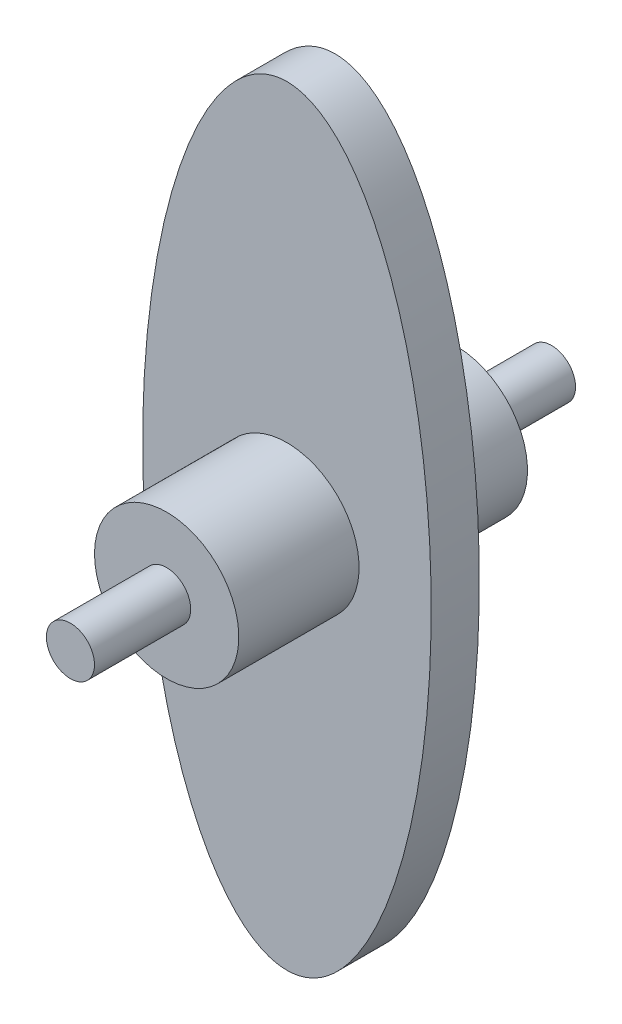
SolidWorks part; units mm, degrees
ref_plane "Front Plane" through (0, 0, 0) normal (0, 0, 1) x (1, 0, 0)
ref_plane "Top Plane" through (0, 0, 0) normal (0, 1, 0) x (1, 0, 0)
ref_plane "Right Plane" through (0, 0, 0) normal (1, 0, 0) x (0, 0, -1)
sketch "Sketch1" plane through (0, 0, 0) normal (0, 0, 1) x (1, 0, 0)
  ellipse E0 centre (0, 0) end of major axis (0, 50.8) minor radius 19.05
  dimension "D1" = 19.05
  dimension "D2" = 50.8
extrude "Boss-Extrude1" add sketch "Sketch1" along normal mid plane 6.35
sketch "Sketch3" plane through (0, 0, 0) normal (0, 0, 1) x (1, 0, 0)
  circle A0 centre (0, 0) radius 9.525
  dimension "D1" = 19.05
extrude "Boss-Extrude3" add sketch "Sketch3" along normal mid plane 38.1
sketch "Sketch4" plane through (0, 0, 0) normal (0, 0, 1) x (1, 0, 0)
  circle A0 centre (0, 0) radius 3.175
  dimension "D1" = 6.35
extrude "Boss-Extrude4" add sketch "Sketch4" along normal mid plane 63.5
